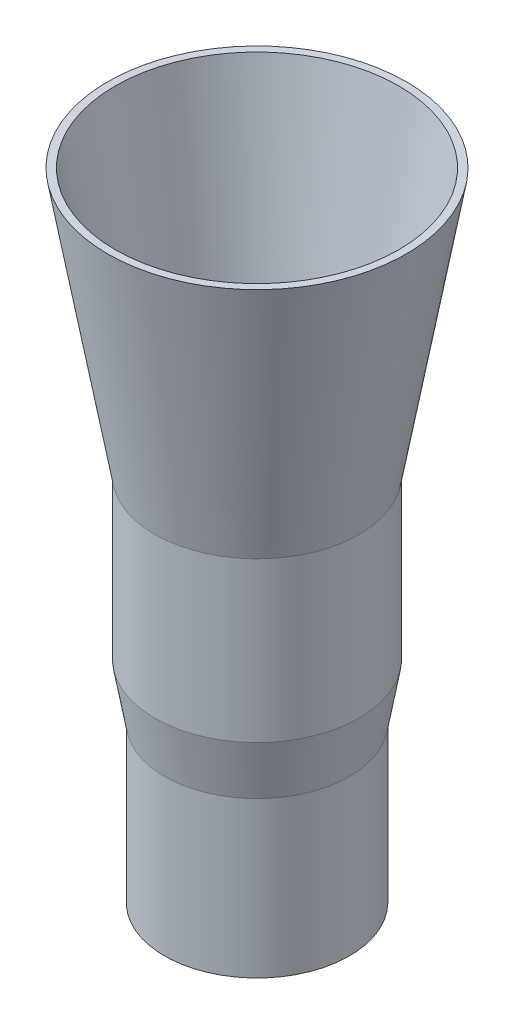
SolidWorks part; units mm, degrees
ref_plane "前视基准面" through (0, 0, 0) normal (0, 0, 1) x (1, 0, 0)
ref_plane "上视基准面" through (0, 0, 0) normal (0, 1, 0) x (1, 0, 0)
ref_plane "右视基准面" through (0, 0, 0) normal (1, 0, 0) x (0, 0, -1)
sketch "草图1" plane through (0, 0, 0) normal (0, 0, 1) x (1, 0, 0)
  line L0 (0, 0) -> (0, 634.4107) construction
  line L1 (0, 0) -> (250, 0)
  line L9 (230, 20) -> (0, 20)
  line L10 (0, 20) -> (0, 0)
  line L11 (250, 0) -> (250, 420)
  line L12 (250, 420) -> (276.449, 570)
  line L13 (230, 20) -> (230, 420)
  line L14 (230, 420) -> (256.449, 570)
  line L15 (256.449, 570) -> (256.449, 1000)
  line L16 (276.449, 570) -> (276.449, 1000)
  line L17 (256.449, 1000) -> (383.4045, 1720)
  line L18 (383.4045, 1720) -> (403.4045, 1720)
  line L19 (403.4045, 1720) -> (276.449, 1000)
  point P10 (550.9479, 1720)
  point P15 (0, 0)
  point P16 (0, 0)
  point P17 (0, 634.4107)
  dimension "D1" = 250
  dimension "D2" = 230
  dimension "D3" = 20
  dimension "D4" = 400
  dimension "D5" = 170
  dimension "D6" = 150
  dimension "D7" = 430
  dimension "D8" = 720
  dimension "D9" = 170
revolve "旋转1" add sketch "草图1" angle 360 about L0
